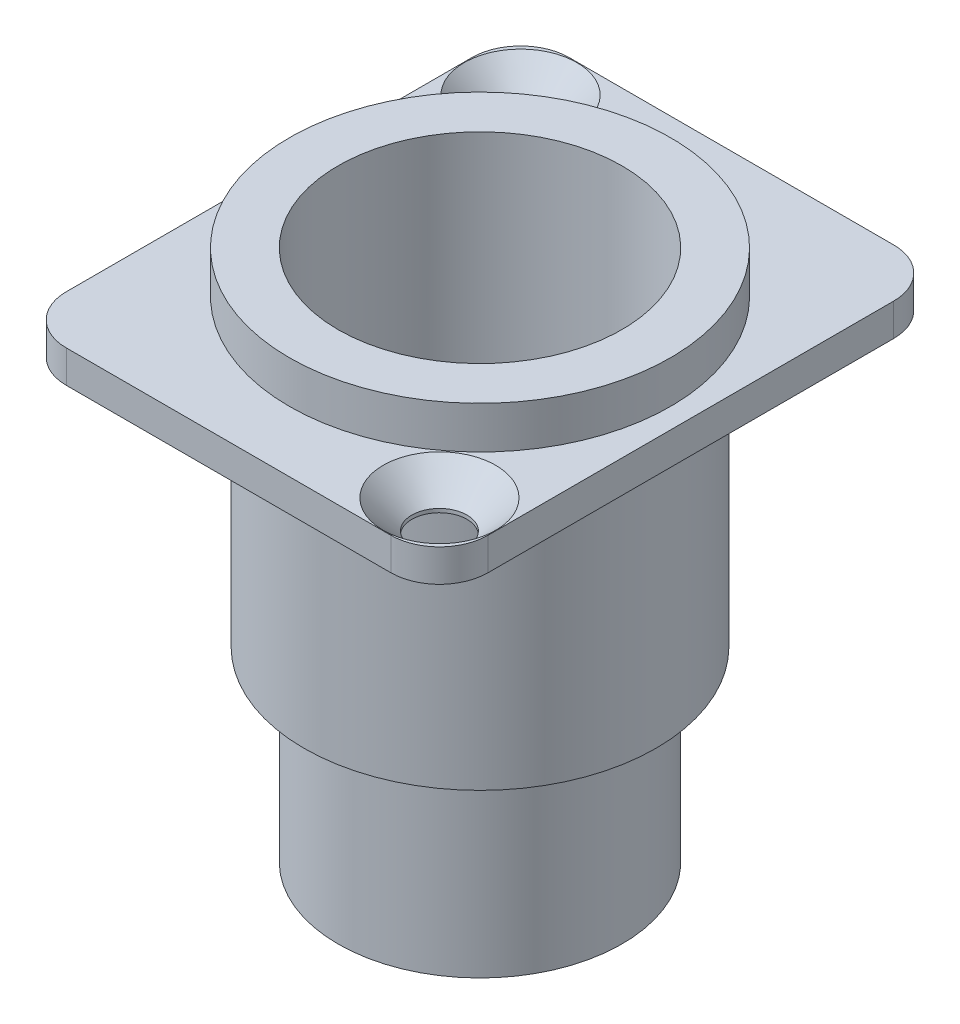
SolidWorks part; units mm, degrees
ref_plane "Alzado" through (0, 0, 0) normal (0, 0, 1) x (1, 0, 0)
ref_plane "Planta" through (0, 0, 0) normal (0, 1, 0) x (1, 0, 0)
ref_plane "Vista lateral" through (0, 0, 0) normal (1, 0, 0) x (0, 0, -1)
sketch "Croquis1" plane through (0, 0, 0) normal (0, 1, 0) x (1, 0, 0)
  line L0 (0, 15.5) -> (0, -15.5) construction
  line L1 (-13, -15.5) -> (13, -15.5)
  line L2 (-13, -15.5) -> (-13, 15.5)
  line L3 (-13, 15.5) -> (13, 15.5)
  line L4 (13, -15.5) -> (13, 15.5)
  line L5 (-13, -15.5) -> (13, 15.5) construction
  line L6 (-13, 15.5) -> (13, -15.5) construction
  line L7 (-13, 0) -> (13, 0) construction
  circle A0 centre (0, 0) radius 8.75
  circle A1 centre (-9.5, 12) radius 1.7
  circle A2 centre (9.5, -12) radius 1.7
  point P0 (0, 0)
  dimension "D3" = 17.5
  dimension "D8" = 3.4
  dimension "D1" = 26
  dimension "D2" = 31
  dimension "D4" = 9.5
  dimension "D5" = 9.5
  dimension "D6" = 12
  dimension "D7" = 12
extrude "Saliente-Extruir1" add sketch "Croquis1" along normal blind 2
fillet "Redondeo1" radius 3 4 edges at (-13, 1, -15.5) (-13, 1, 15.5) (13, 1, 15.5) (13, 1, -15.5)
sketch "Croquis2" plane through (0, 2, 0) normal (0, 1, 0) x (1, 0, 0)
  circle A0 centre (0, 0) radius 11.75
  circle A1 centre (0, 0) radius 8.75 construction
  circle A2 centre (0, 0) radius 8.75
  dimension "D1" = 23.5
extrude "Saliente-Extruir2" add sketch "Croquis2" along normal blind 2.6
sketch "Croquis3" plane through (0, 0, 0) normal (0, -1, 0) x (1, 0, 0)
  circle A0 centre (0, 0) radius 10.85
  circle A1 centre (0, 0) radius 8.75 construction
  circle A2 centre (0, 0) radius 8.75
  dimension "D1" = 21.7
extrude "Saliente-Extruir3" add sketch "Croquis3" along normal blind 16.7
hole_wizard "Avellanado para tornillos con cabeza avellanada de clavija de M31" positions "Croquis4" profile "Croquis5" countersink size "M3" standard "DIN"
sketch "Croquis4" plane through (0, 2, 0) normal (0, 1, 0) x (1, 0, 0)
  point P0 (9.5, -12)
  point P3 (-9.5, 12)
sketch "Croquis5" plane through (9.5, 2, 12) normal (1, 0, 0) x (0, 0, 1)
  line L0 (0, 0) -> (0, 16.0215)
  line L1 (0, 16.0215) -> (1.7, 15)
  line L2 (1.7, 15) -> (1.7, 1.77)
  line L3 (1.7, 1.77) -> (3.47, 0)
  line L5 (3.47, 0) -> (0, 0)
  line L6 (-1.7, 1.77) -> (-3.47, 0) construction
  line L10 (0, 16.0215) -> (-1.7, 15) construction
  line L11 (0, -6.35) -> (0, 107.95) construction
  dimension "Diámetro de taladro" = 3.4
  dimension "Profundidad de taladro" = 15
  dimension "Ángulo de avellanado cercano" = 6.94
  dimension "Ángulo de avellanado lejano" = 90
  dimension "Ángulo de perforador" = 118
sketch "Croquis6" plane through (0, 4.6, 0) normal (0, 1, 0) x (1, 0, 0)
  circle A0 centre (0, 0) radius 8.75
extrude "Saliente-Extruir4" add sketch "Croquis6" against normal blind 32.8 separate body
sketch "Croquis7" plane through (0, 4.6, 0) normal (0, 1, 0) x (1, 0, 0)
  line L1 (-6.35, -2.7) -> (6.35, -2.7)
  line L2 (-6.35, -2.7) -> (-6.35, 2.7)
  line L3 (-6.35, 2.7) -> (6.35, 2.7)
  line L4 (6.35, -2.7) -> (6.35, 2.7)
  line L5 (-6.35, -2.7) -> (6.35, 2.7) construction
  line L6 (-6.35, 2.7) -> (6.35, -2.7) construction
  point P0 (0, 0)
  dimension "D1" = 12.7
  dimension "D2" = 5.4
extrude "Cortar-Extruir1" cut sketch "Croquis7" against normal blind 10
sketch "Croquis8" plane through (0, -28.2, 0) normal (0, -1, 0) x (1, 0, 0)
  line L4 (6.35, -2.7) -> (6.35, 2.7)
  line L5 (-6.35, -2.7) -> (6.35, -2.7)
  line L6 (-6.35, 2.7) -> (-6.35, -2.7)
  line L7 (6.35, 2.7) -> (-6.35, 2.7)
  line L8 (6.35, -2.7) -> (6.35, 2.7)
  line L9 (-6.35, -2.7) -> (6.35, -2.7)
  line L10 (-6.35, 2.7) -> (-6.35, -2.7)
  line L11 (6.35, 2.7) -> (-6.35, 2.7)
  dimension "D1" = 0
extrude "Cortar-Extruir2" cut sketch "Croquis8" against normal blind 10
sketch "Croquis9" plane through (0, -28.2, 0) normal (0, -1, 0) x (1, 0, 0)
  line L0 (6.15, 2.5) -> (-6.15, 2.5)
  line L1 (-6.15, 2.5) -> (-6.15, -2.5)
  line L2 (-6.15, -2.5) -> (6.15, -2.5)
  line L3 (6.15, -2.5) -> (6.15, 2.5)
  line L4 (6.35, 2.7) -> (-6.35, 2.7)
  line L5 (-6.35, 2.7) -> (-6.35, -2.7)
  line L6 (-6.35, -2.7) -> (6.35, -2.7)
  line L7 (6.35, -2.7) -> (6.35, 2.7)
  line L8 (6.35, 2.7) -> (-6.35, 2.7)
  line L9 (-6.35, 2.7) -> (-6.35, -2.7)
  line L10 (-6.35, -2.7) -> (6.35, -2.7)
  line L11 (6.35, -2.7) -> (6.35, 2.7)
  dimension "D1" = 0
  dimension "D2" = 0.2
extrude "Saliente-Extruir5" add sketch "Croquis9" against normal blind 10 separate body
sketch "Croquis10" plane through (0, 4.6, 0) normal (0, 1, 0) x (1, 0, 0)
  line L0 (6.15, -2.5) -> (6.15, 2.5)
  line L1 (6.15, 2.5) -> (-6.15, 2.5)
  line L2 (-6.15, 2.5) -> (-6.15, -2.5)
  line L3 (-6.15, -2.5) -> (6.15, -2.5)
  line L4 (6.35, -2.7) -> (6.35, 2.7)
  line L5 (6.35, 2.7) -> (-6.35, 2.7)
  line L6 (-6.35, 2.7) -> (-6.35, -2.7)
  line L7 (-6.35, -2.7) -> (6.35, -2.7)
  line L8 (6.35, -2.7) -> (6.35, 2.7)
  line L9 (6.35, 2.7) -> (-6.35, 2.7)
  line L10 (-6.35, 2.7) -> (-6.35, -2.7)
  line L11 (-6.35, -2.7) -> (6.35, -2.7)
  dimension "D1" = 0
  dimension "D2" = 0.2
extrude "Saliente-Extruir6" add sketch "Croquis10" against normal blind 10 separate body
sketch "Croquis11" plane through (0, -5.4, 0) normal (0, 1, 0) x (1, 0, 0)
  line L1 (-6.15, -2.5) -> (6.15, -2.5)
  line L2 (-6.15, -2.5) -> (-6.15, 2.5)
  line L3 (-6.15, 2.5) -> (6.15, 2.5)
  line L4 (6.15, -2.5) -> (6.15, 2.5)
  line L5 (-6.15, -2.5) -> (6.15, 2.5) construction
  line L6 (-6.15, 2.5) -> (6.15, -2.5) construction
  point P0 (0, 0)
extrude "Saliente-Extruir7" add sketch "Croquis11" along normal blind 0.7 separate body
sketch "Croquis12" plane through (0, -18.2, 0) normal (0, -1, 0) x (1, 0, 0)
  line L1 (6.15, -2.5) -> (-6.15, -2.5)
  line L2 (6.15, -2.5) -> (6.15, 2.5)
  line L3 (6.15, 2.5) -> (-6.15, 2.5)
  line L4 (-6.15, -2.5) -> (-6.15, 2.5)
  line L5 (6.15, -2.5) -> (-6.15, 2.5) construction
  line L6 (6.15, 2.5) -> (-6.15, -2.5) construction
  point P0 (0, 0)
extrude "Saliente-Extruir8" add sketch "Croquis12" along normal blind 0.7 separate body
sketch "Croquis13" plane through (0, -4.7, 0) normal (0, 1, 0) x (1, 0, 0)
  line L0 (-6.15, -2.5) -> (6.15, -2.5) construction
  line L1 (-5.5, -1.7) -> (5.5, -1.7)
  line L2 (-5.5, -1.7) -> (-5.5, 0.3)
  line L3 (-5.5, 0.3) -> (5.5, 0.3)
  line L4 (5.5, -1.7) -> (5.5, 0.3)
  line L5 (-5.5, -1.7) -> (5.5, 0.3) construction
  line L6 (-5.5, 0.3) -> (5.5, -1.7) construction
  point P0 (0, -0.7)
  dimension "D1" = 11
  dimension "D2" = 2
  dimension "D3" = 0.8
extrude "Saliente-Extruir9" add sketch "Croquis13" along normal blind 9 separate body
sketch "Croquis14" plane through (0, -18.9, 0) normal (0, -1, 0) x (1, 0, 0)
  line L4 (5.5, -0.3) -> (5.5, 1.7)
  line L5 (-5.5, -0.3) -> (5.5, -0.3)
  line L6 (-5.5, 1.7) -> (-5.5, -0.3)
  line L7 (5.5, 1.7) -> (-5.5, 1.7)
  line L8 (5.5, -0.3) -> (5.5, 1.7)
  line L9 (-5.5, -0.3) -> (5.5, -0.3)
  line L10 (-5.5, 1.7) -> (-5.5, -0.3)
  line L11 (5.5, 1.7) -> (-5.5, 1.7)
  dimension "D1" = 0
extrude "Saliente-Extruir10" add sketch "Croquis14" along normal blind 9 separate body
chamfer "Chaflán1" distance 0.5 angle 45 4 edges at (0, 4.3, 1.7) (-5.5, 4.3, 0.7) (0, 4.3, -0.3) (5.5, 4.3, 0.7)
chamfer "Chaflán2" distance 0.5 angle 45 4 edges at (5.5, -27.9, 0.7) (0, -27.9, -0.3) (-5.5, -27.9, 0.7) (0, -27.9, 1.7)
sketch "Sketch1" plane through (0, 4.6, 0) normal (0, 1, 0) x (1, 0, 0)
  circle A0 centre (0, 0) radius 8.75
extrude "Cut-Extrude1" cut sketch "Sketch1" against normal blind 20
